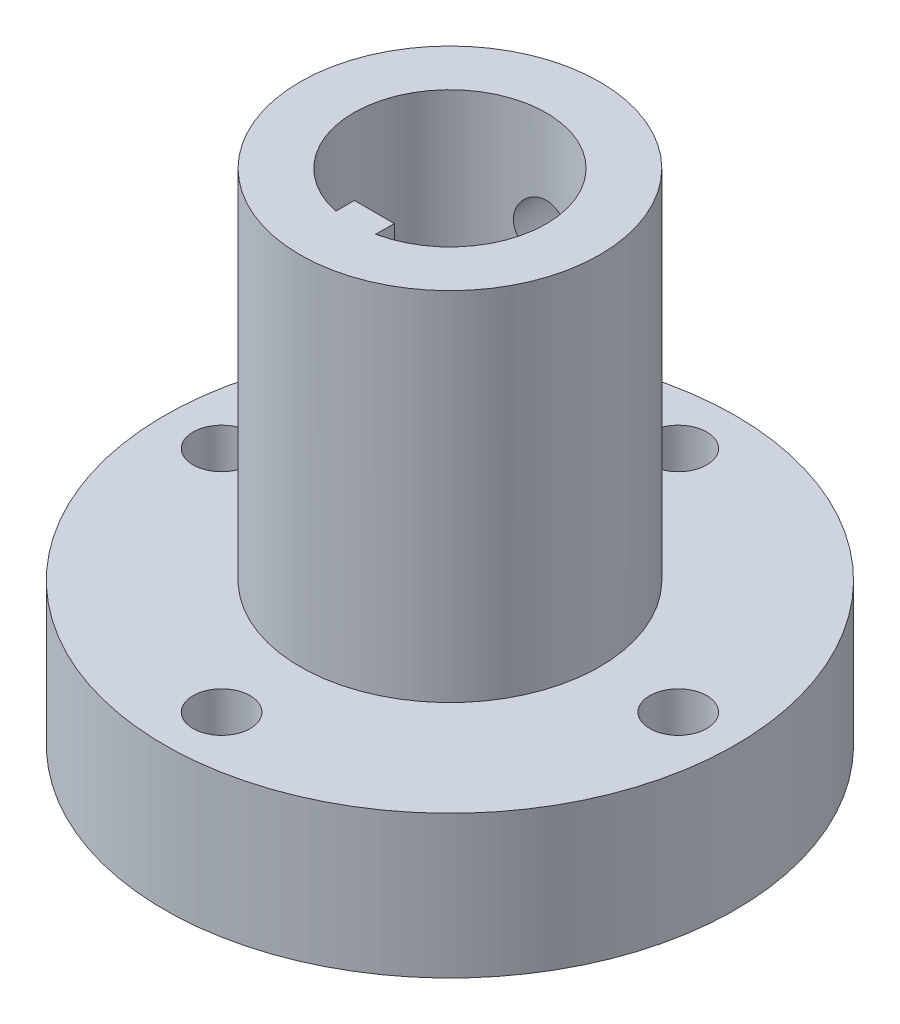
SolidWorks part; units mm, degrees
ref_plane "Front Plane" through (0, 0, 0) normal (0, 0, 1) x (1, 0, 0)
ref_plane "Top Plane" through (0, 0, 0) normal (0, 1, 0) x (1, 0, 0)
ref_plane "Right Plane" through (0, 0, 0) normal (1, 0, 0) x (0, 0, -1)
sketch "Sketch1" plane through (0, 0, 0) normal (0, 1, 0) x (1, 0, 0)
  circle A0 centre (0, 0) radius 10.5
  dimension "D1" = 21
extrude "Boss-Extrude1" add sketch "Sketch1" along normal blind 25 contours A0
sketch "Sketch4" plane through (0, 0, 0) normal (0, -1, 0) x (1, 0, 0)
  circle A0 centre (0, 0) radius 20
  dimension "D1" = 40
extrude "Boss-Extrude2" add sketch "Sketch4" along normal blind 10
sketch "Sketch5" plane through (0, 25, 0) normal (0, 1, 0) x (1, 0, 0)
  circle A0 centre (0, 0) radius 6.75
  dimension "D1" = 13.5
extrude "Cut-Extrude1" cut sketch "Sketch5" against normal through all
sketch "Sketch6" plane through (0, 25, 0) normal (0, 1, 0) x (1, 0, 0)
  line L0 (0, 0) -> (0, -6.75) construction
  line L1 (-1.4, -5.3) -> (1.4, -5.3)
  line L2 (-1.4, -5.3) -> (-1.4, -8.2)
  line L3 (-1.4, -8.2) -> (1.4, -8.2)
  line L4 (1.4, -5.3) -> (1.4, -8.2)
  line L5 (-1.4, -5.3) -> (1.4, -8.2) construction
  line L6 (-1.4, -8.2) -> (1.4, -5.3) construction
  circle A0 centre (0, 0) radius 6.75 construction
  point P0 (0, -6.75)
  dimension "D1" = 2.8
  dimension "D2" = 2.9
extrude "Boss-Extrude3" add sketch "Sketch6" against normal through all
sketch "Sketch7" plane through (0, -10, 0) normal (0, -1, 0) x (1, 0, 0)
  line L0 (0, 16) -> (0, 20) construction
  circle A0 centre (0, 16) radius 2
  circle A1 centre (16, 0) radius 2
  circle A2 centre (0, -16) radius 2
  circle A3 centre (-16, 0) radius 2
  circle A4 centre (0, 0) radius 20 construction
  point P11 (0, 0)
  dimension "D1" = 4
  dimension "D3" = 4
  dimension "D2" = 4
extrude "Cut-Extrude2" cut sketch "Sketch7" against normal up to vertex (10 mm away) up to point (0, 0, 0)
sketch "Sketch8" plane through (0, 0, 0) normal (0, 0, 1) x (1, 0, 0)
  circle A0 centre (0, 17.6873) radius 2
  dimension "D1" = 4
extrude "Cut-Extrude3" cut sketch "Sketch8" against normal blind 20
